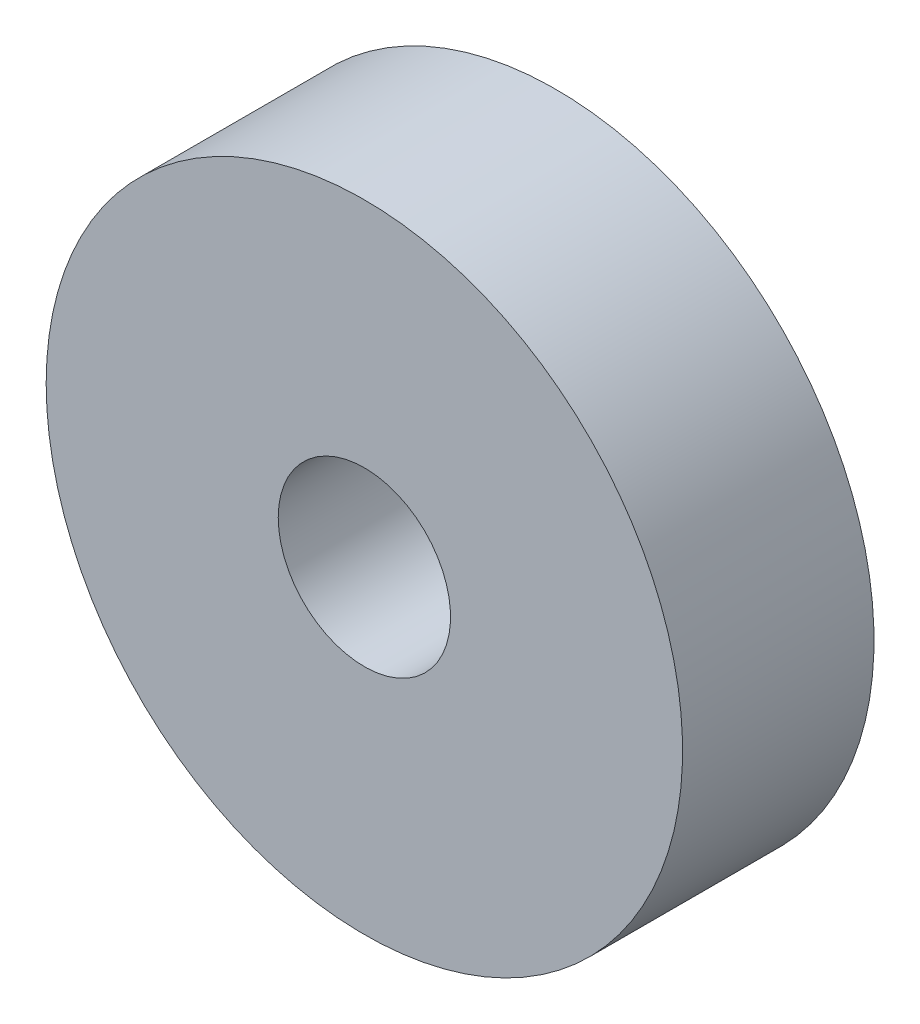
SolidWorks part; units mm, degrees
ref_plane "前视基准面" through (0, 0, 0) normal (0, 0, 1) x (1, 0, 0)
ref_plane "上视基准面" through (0, 0, 0) normal (0, 1, 0) x (1, 0, 0)
ref_plane "右视基准面" through (0, 0, 0) normal (1, 0, 0) x (0, 0, -1)
ref_plane "基准面1" through (0, -0.0002, 0) normal (0, -1, 0) x (1, 0, 0)
sketch "草图1" plane through (0, -0.0002, 0) normal (0, -1, 0) x (1, 0, 0)
  line L0 (1.35, 0.3958) -> (4.9869, 0.3958)
  line L1 (4.9869, 0.3958) -> (4.9869, 3.3958)
  line L2 (4.9869, 3.3958) -> (1.35, 3.3958)
  line L3 (1.35, 3.3958) -> (1.35, 0.3958)
  line L4 (-0.0002, 3.3958) -> (-0.0002, 0.3958) construction
revolve "旋转1" add sketch "草图1" angle 360 about L4
